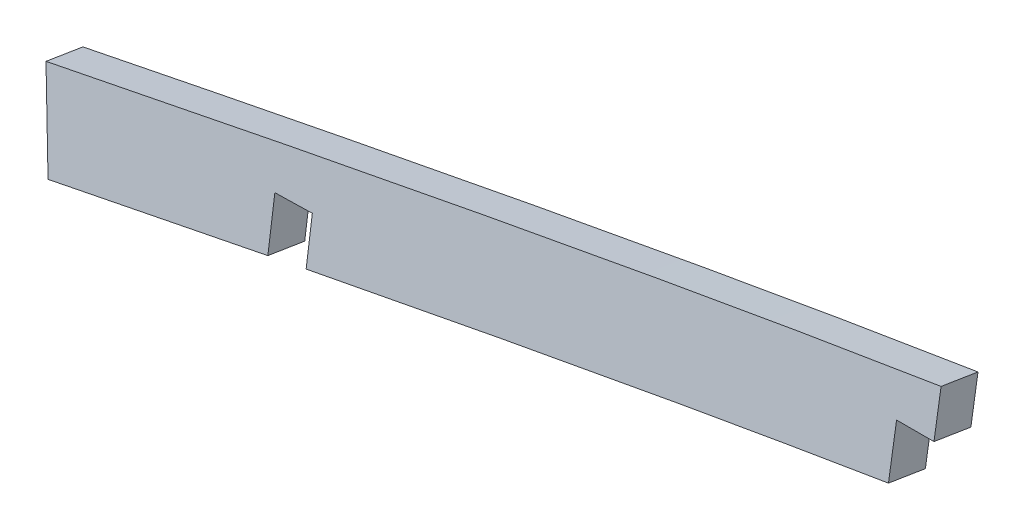
SolidWorks part; units mm, degrees
material "Balsa"
ref_plane "Front Plane" through (0, 0, 0) normal (0, 0, 1) x (1, 0, 0)
ref_plane "Top Plane" through (0, 0, 0) normal (0, 1, 0) x (1, 0, 0)
ref_plane "Right Plane" through (0, 0, 0) normal (1, 0, 0) x (0, 0, -1)
sketch "Sketch3" plane through (0, -90.1866, -561.9284) normal (0, 0.1585, 0.9874) x (1, 0, 0)
  line L1 (371.221, 137.8278) -> (374.396, 137.8278) construction
  line L2 (374.396, 137.8278) -> (374.396, 141.6327)
  line L3 (371.221, 137.8278) -> (374.396, 137.8278)
  line L5 (300.3557, 129.3322) -> (301.7175, 121.8349)
  line L6 (371.221, 141.6326) -> (371.221, 137.8278)
  line L7 (371.221, 137.8278) -> (371.221, 134.0113)
  line L8 (371.221, 137.8278) -> (371.221, 133.4768)
  spline S1 degree 3 poles (374.396, 141.6327) (365.3782, 140.3519) (356.3788, 138.9571) (338.402, 136.0307) (329.4247, 134.4983) (313.7508, 131.7481) (307.0517, 130.5484) (300.3557, 129.3322) knots 0 0 0 0 0.25 0.25 0.5 0.5 0.686814 0.686814 0.686814 0.686814
  spline S2 degree 1 poles (375.4675, 134.0884) (301.7175, 121.8349) knots 0 0 1 1 construction
  spline S3 degree 3 poles (375.4675, 134.0884) (369.3125, 133.2142) (357.0261, 131.3594) (338.5824, 128.3395) (320.1492, 125.1537) (307.8584, 122.9503) (301.7175, 121.8349) knots 0 0 0 0 0.171704 0.343407 0.515111 0.686814 0.686814 0.686814 0.686814 only from (371.221, 133.4768) to (301.7175, 121.8349)
  spline S4 degree 3 poles (375.4675, 134.0884) (374.4045, 133.9374) (372.9901, 133.7344) (371.5748, 133.5284) (371.221, 133.4768) knots 0 0 0 0 0.029644 0.039525 0.039525 0.039525 0.039525 construction
  dimension "D1" = 7.62
extrude "Boss-Extrude1" add sketch "Sketch3" along normal blind 3.175
sketch "Sketch4" plane through (0, -90.1866, -561.9284) normal (0, -0.1585, -0.9874) x (-1, 0, 0)
  line L0 (-319.7737, 129.3843) -> (-319.8499, 125.6302)
  line L1 (-323.0254, 125.6388) -> (-323.0254, 123.8079)
  line L2 (-322.948, 129.4488) -> (-323.0243, 125.6941)
  line L3 (-322.948, 129.4488) -> (-323.0254, 125.6388)
  line L4 (-319.7737, 129.3843) -> (-319.8611, 125.0832)
  line L5 (-322.948, 129.4488) -> (-319.7737, 129.3843)
  line L7 (-319.8611, 123.7346) -> (-319.8611, 125.0832)
  line L8 (-319.8611, 123.7346) -> (-323.0254, 123.8079)
  spline S0 degree 3 poles (-301.7175, 121.8349) (-307.8584, 122.9503) (-320.1492, 125.1537) (-338.5824, 128.3396) (-355.6116, 131.1278) (-366.4856, 132.7854) (-371.221, 133.4768) knots 0 0 0 0 0.171704 0.343407 0.515111 0.647311 0.647311 0.647311 0.647311 construction
  spline S5 degree 3 poles (-301.7175, 121.8349) (-307.8584, 122.9503) (-320.1492, 125.1537) (-338.5824, 128.3396) (-355.6116, 131.1278) (-366.4856, 132.7854) (-371.221, 133.4768) knots 0 0 0 0 0.171704 0.343407 0.515111 0.647311 0.647311 0.647311 0.647311 construction
  dimension "D1" = 3.81
extrude "Cut-Extrude1" cut sketch "Sketch4" against normal through all
